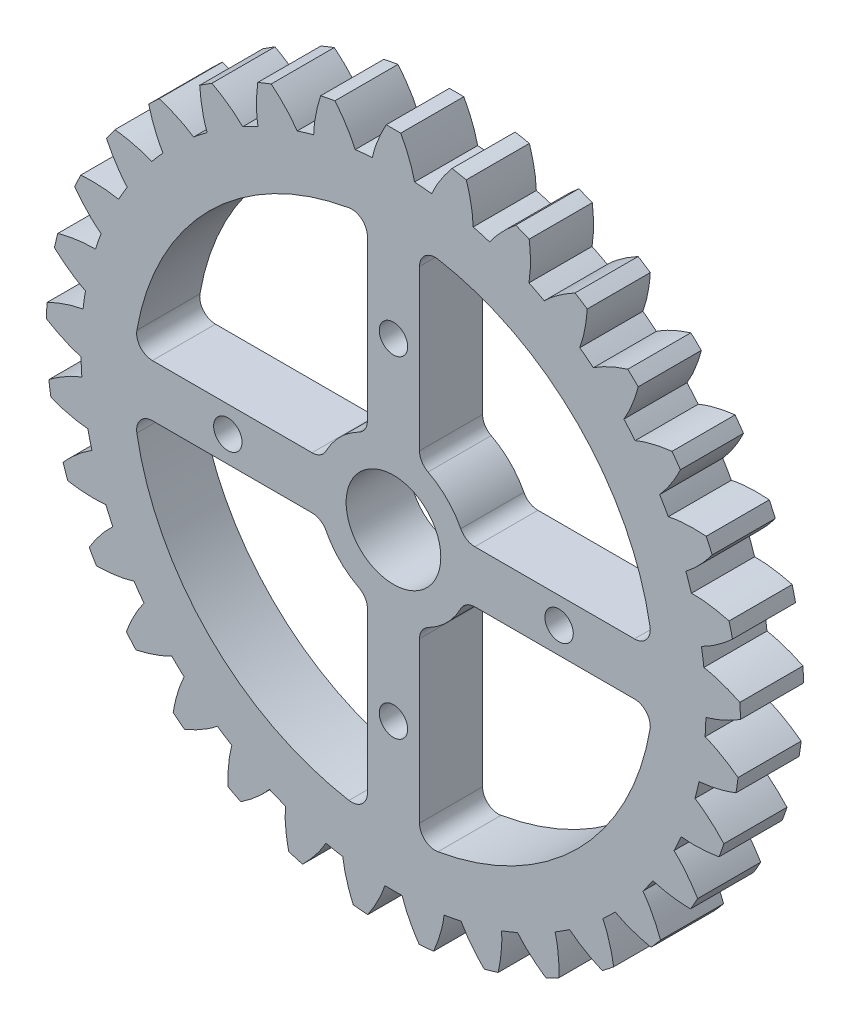
SolidWorks part; units mm, degrees
material "ABS"
ref_plane "Front Plane" through (0, 0, 0) normal (0, 0, 1) x (1, 0, 0)
ref_plane "Top Plane" through (0, 0, 0) normal (0, 1, 0) x (1, 0, 0)
ref_plane "Right Plane" through (0, 0, 0) normal (1, 0, 0) x (0, 0, -1)
sketch "Definition Drawing" plane through (0, 0, 0) normal (0, 0, 1) x (1, 0, 0)
  line L0 (22.0085, 0) -> (20.0085, 0) construction
  line L1 (0, 0) -> (-9.2041, 16.6677) construction
  line L2 (0, 0) -> (0, 22.0085) construction
  line L3 (0, 0) -> (1.4305, 18.9863) construction
  line L4 (-9.2041, 16.6677) -> (0.4589, 22.0037) construction
  line L5 (0, 0) -> (0.9497, 20.987) construction
  line L6 (0, 0) -> (0.9996, 20.9847) construction
  line L7 (0, 0) -> (-6.7003, 17.8222) construction
  line L8 (-6.7003, 17.8222) -> (1.0489, 20.7356) construction
  line L9 (0, 0) -> (-4.056, 18.6031) construction
  line L10 (-4.056, 18.6031) -> (1.3365, 19.7788) construction
  line L11 (0, 0) -> (-1.3267, 18.9938) construction
  line L12 (-1.3267, 18.9938) -> (1.4262, 19.1861) construction
  circle A0 centre (0, 0) radius 19.0401 construction
  circle A1 centre (0, 0) radius 20.0085 construction
  circle A2 centre (0, 0) radius 21.0085 construction
  circle A3 centre (0, 0) radius 22.0085 construction
  circle A4 centre (0, 0) radius 19.8085 construction
  arc A5 (0.9497, 20.987) -> (0.9996, 20.9847) centre (0, 0) cw construction
  spline S0 degree 3 poles (1.4305, 18.9863) (1.4359, 19.2532) (1.2698, 20.313) (0.842, 21.3036) (0.4589, 22.0037) knots 0 0 0 0 0.250017 1 1 1 1 construction
  point P13 (21.0085, 0)
  dimension "D4" = 42.0169
  dimension "D5" = 38.0802
  dimension "D1" = 2
  dimension "D2" = 0.2
  dimension "D3" = 2.727
  dimension "D6" = 0.05
  dimension "D7" = 33.217
  dimension "D11" = 8.2788
  dimension "D12" = 5.5192
  dimension "D13" = 2.7596
  dimension "D8" = 24.913
  dimension "D9" = 16.608
  dimension "D10" = 8.304
sketch "Sketch5" plane through (0, 0, 0) normal (0, 0, 1) x (1, 0, 0)
  circle A1 centre (0, 0) radius 19.8085
  circle A2 centre (0, 0) radius 1.5
  circle A3 centre (0, 0) radius 19.8085 construction
  dimension "D1" = 3
extrude "Extrude Body" add sketch "Sketch5" along normal mid plane 4
sketch "Sketch6" plane through (0, 0, 0) normal (0, 0, 1) x (1, 0, 0)
  line L0 (0, 22.0085) -> (0, 0) construction
  line L4 (1.4305, 18.9863) -> (0.1127, 1.4958)
  line L5 (0, 0) -> (1.4305, 18.9863) construction
  line L6 (-1.4305, 18.9863) -> (-0.1127, 1.4958)
  arc A0 (0.4589, 22.0037) -> (-0.4589, 22.0037) centre (0, 0) ccw
  arc A3 (0.1127, 1.4958) -> (-0.1127, 1.4958) centre (0, 0) ccw
  circle A4 centre (0, 0) radius 1.5 construction
  spline S0 degree 3 poles (1.4305, 18.9863) (1.4359, 19.2532) (1.2698, 20.313) (0.842, 21.3036) (0.4589, 22.0037) knots 0 0 0 0 0.250017 1 1 1 1
  spline S1 degree 3 poles (-1.4305, 18.9863) (-1.4359, 19.2532) (-1.2698, 20.313) (-0.842, 21.3036) (-0.4589, 22.0037) knots 0 0 0 0 0.250017 1 1 1 1
extrude "Extrude Tooth" add sketch "Sketch6" along normal mid plane 4
pattern_circular "CirPattern1" count 33 over 360 about axis through (0, 0, 2) along (0, 0, -1) of "Extrude Tooth"
sketch "Sketch8" plane through (0, 0, 0) normal (0, 0, 1) x (1, 0, 0)
  line L6 (0, 22.0085) -> (0, 0) construction
  line L7 (0, 0) -> (22.0085, 0) construction
  line L8 (1.65, 15.2804) -> (1.65, 5.1592)
  line L9 (5.1592, 1.65) -> (15.2804, 1.65)
  circle A2 centre (0, 0) radius 22.0085 construction
  arc A20 (16.2657, 2.8209) -> (2.8209, 16.2657) centre (0, 0) ccw
  circle A21 centre (0, 0) radius 19.8085 construction
  arc A23 (15.2804, 1.65) -> (16.2657, 2.8209) centre (15.2804, 2.65) ccw
  arc A24 (5.1592, 1.65) -> (4.2697, 2.1931) centre (5.1592, 2.65) cw
  arc A25 (1.65, 5.1592) -> (2.1931, 4.2697) centre (2.65, 5.1592) ccw
  arc A26 (1.65, 15.2804) -> (2.8209, 16.2657) centre (2.65, 15.2804) cw
  arc A27 (4.2697, 2.1931) -> (2.1931, 4.2697) centre (0, 0) ccw
  circle A28 centre (0, 0) radius 1.5 construction
  dimension "D6" = 1
  dimension "D4" = 3.3
  dimension "D5" = 3.3
  dimension "D2" = 3.3
  dimension "D3" = 90
extrude "Cut Spoke" cut sketch "Sketch8" against normal through all and the other way through all
pattern_circular "Pattern Spokes" count 4 over 360 about axis through (0, 0, 0) along (0, 0, 1) of "Cut Spoke"
sketch "Sketch9" plane through (0, 0, 2) normal (0, 0, 1) x (1, 0, 0)
  line L0 (0, 0) -> (0, 10.5) construction
  circle A0 centre (0, 10.5) radius 0.9
  dimension "D1" = 1.8
  dimension "D2" = 10.5
extrude "Cut-Extrude1" cut sketch "Sketch9" against normal through all
pattern_circular "CirPattern2" count 4 over 360 about axis through (0, 0, 0) along (0, 0, 1) of "Cut-Extrude1"
sketch "Sketch10" plane through (0, 0, 2) normal (0, 0, 1) x (1, 0, 0)
  circle A0 centre (0, 0) radius 3
  dimension "D1" = 6
extrude "Cut-Extrude2" cut sketch "Sketch10" against normal up to surface (4 mm away)
equation "\"nTeeth\" = 33"
equation "\"xThickness\"= 4"
equation "\"dShaft\"= 3"
equation "\"aPressure\"=25"
equation "\"pitch\"= 4"
equation "\"rHeight\"= 2"
equation "\"rClearance\"= 0.2"
equation "\"xClearance\"=0.05"
equation "\"rFillet\"= 1"
equation "\"nSpokes\" = 4'rounds up"
equation "\"dPitch\"= \"nTeeth\" * \"pitch\" / pi"
equation "\"xWall\"= IIF ( \"nTeeth\" > 30 , \"nTeeth\" / 10 , 3 )"
equation "\"dBase\"= \"dPitch\" * cos ( \"aPressure\" )"
equation "\"rOuter\"= \"dPitch\" / 2 + \"rHeight\" / 2"
equation "\"xInvolute\"= sqr ( \"rOuter\" ^ 2 - ( \"dBase\" / 2 ) ^ 2 )"
equation "\"aInvolute\"= 360 * \"xInvolute\" / ( \"dBase\" / 2 ) / 2 / pi"
equation "\"D1@Definition Drawing\" = \"rHeight\""
equation "\"D2@Definition Drawing\" = \"rClearance\""
equation "\"D4@Definition Drawing\" = \"dPitch\""
equation "\"D6@Definition Drawing\" = \"xClearance\""
equation "\"D5@Definition Drawing\" = \"dBase\""
equation "\"D7@Definition Drawing\" = \"aInvolute\""
equation "\"D11@Definition Drawing\" = \"xInvolute\" * 0.75"
equation "\"D12@Definition Drawing\" = \"xInvolute\" * 0.5"
equation "\"D13@Definition Drawing\" = \"xInvolute\" * 0.25"
equation "\"D8@Definition Drawing\" = \"aInvolute\" * 0.75"
equation "\"D9@Definition Drawing\" = \"aInvolute\" * 0.5"
equation "\"D10@Definition Drawing\" = \"aInvolute\" * 0.25"
equation "\"D1@Extrude Body\"=\"xThickness\""
equation "\"D1@Sketch5\"=\"dShaft\""
equation "\"D3@Definition Drawing\" = 360 / \"nTeeth\" / 2 / 2"
equation "\"D5@Sketch8\"=\"xWall\""
equation "\"D1@Sketch8\"=\"xWall\""
equation "\"D4@Sketch8\"=\"xWall\""
equation "\"D6@Sketch8\"=\"rFillet\""
equation "\"D1@Pattern Spokes\" = \"nSpokes\""
equation "\"rHub\"= IIF ( \"xWall\" * \"nSpokes\" / 6 > \"xWall\" , \"xWall\" * \"nSpokes\" / 6 , \"xWall\" )"
equation "\"D2@Sketch8\"=\"rHub\""
equation "\"D3@Sketch8\"=360/\"nSpokes\""
equation "\"D1@Extrude Tooth\" = \"xThickness\""
equation "\"D1@CirPattern1\"=\"nTeeth\""
